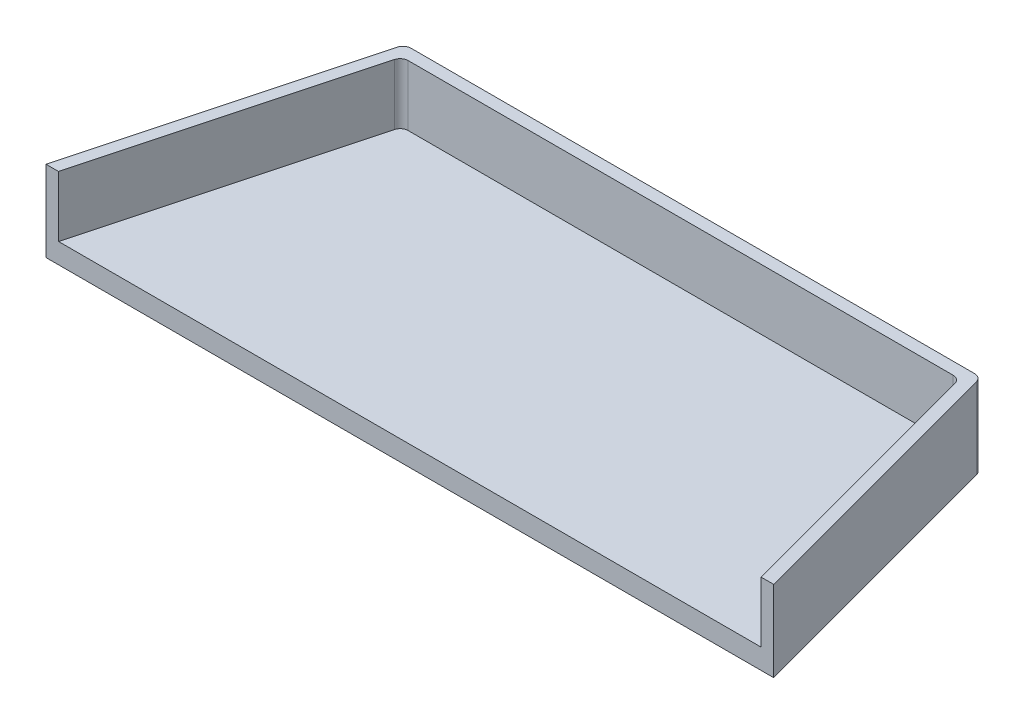
SolidWorks part; units mm, degrees
ref_plane "Front Plane" through (0, 0, 0) normal (0, 0, 1) x (1, 0, 0)
ref_plane "Top Plane" through (0, 0, 0) normal (0, 1, 0) x (1, 0, 0)
ref_plane "Right Plane" through (0, 0, 0) normal (1, 0, 0) x (0, 0, -1)
sketch "Sketch1" plane through (0, 0, 0) normal (0, 1, 0) x (1, 0, 0)
  line L0 (0, 0) -> (0, 70) construction
  line L1 (71.2436, 70) -> (-71.2436, 70)
  line L2 (-71.2436, 70) -> (-90, 0)
  line L3 (-90, 0) -> (90, 0)
  line L4 (71.2436, 70) -> (90, 0)
  dimension "D1" = 90
  dimension "D2" = 70
  dimension "D3" = 75
extrude "Boss-Extrude1" add sketch "Sketch1" along normal blind 5
sketch "Sketch2" plane through (0, 5, 0) normal (0, 1, 0) x (1, 0, 0)
  line L0 (68.9416, 67) -> (-68.9416, 67)
  line L1 (-68.9416, 67) -> (-86.8942, 0)
  line L3 (86.8942, 0) -> (68.9416, 67)
  line L4 (90, 0) -> (71.2436, 70)
  line L5 (71.2436, 70) -> (-71.2436, 70)
  line L6 (-71.2436, 70) -> (-90, 0)
  line L7 (-90, 0) -> (90, 0)
  line L8 (90, 0) -> (71.2436, 70)
  line L9 (71.2436, 70) -> (-71.2436, 70)
  line L10 (-71.2436, 70) -> (-90, 0)
  line L12 (-68.9416, 67) -> (-86.0903, 3) construction
  line L13 (86.0903, 3) -> (68.9416, 67) construction
  line L14 (-86.0903, 3) -> (86.0903, 3) construction
  line L16 (-90, 0) -> (90, 0) construction
  line L17 (90, 0) -> (86.8942, 0)
  line L18 (-86.8942, 0) -> (-90, 0)
  dimension "D1" = 0
  dimension "D2" = 3
extrude "Boss-Extrude2" add sketch "Sketch2" along normal blind 15
fillet "Fillet1" radius 2 4 edges at (-71.2436, 10, -70) (-68.9416, 12.5, -67) (68.9416, 12.5, -67) (71.2436, 10, -70)
